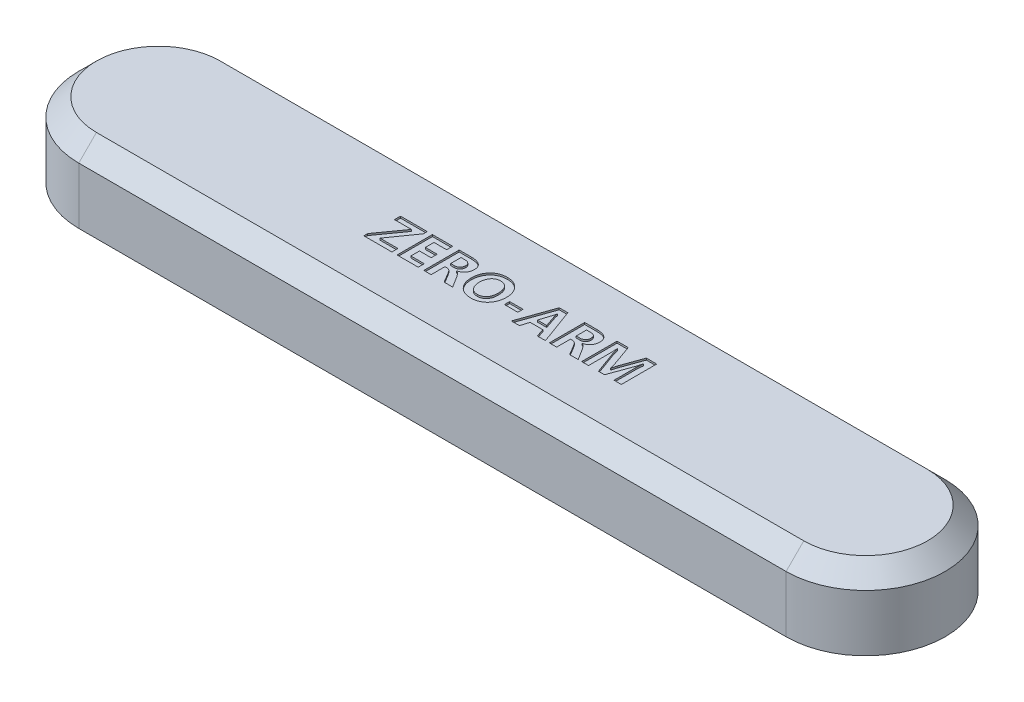
SolidWorks part; units mm, degrees
ref_plane "前视基准面" through (0, 0, 0) normal (0, 0, 1) x (1, 0, 0)
ref_plane "上视基准面" through (0, 0, 0) normal (0, 1, 0) x (1, 0, 0)
ref_plane "右视基准面" through (0, 0, 0) normal (1, 0, 0) x (0, 0, -1)
other "Configuration Table"
sketch "草图1" plane through (0, 0, 0) normal (0, 1, 0) x (1, 0, 0)
  line L1 (-100, 22.5) -> (100, 22.5)
  line L2 (-100, 22.5) -> (-100, -22.5)
  line L3 (-100, -22.5) -> (100, -22.5)
  line L4 (100, 22.5) -> (100, -22.5)
  line L5 (-100, 22.5) -> (100, -22.5) construction
  line L6 (-100, -22.5) -> (100, 22.5) construction
  circle A0 centre (-100, 0) radius 22.5
  circle A1 centre (100, 0) radius 22.5
  point P0 (0, 0)
  dimension "D1" = 200
  dimension "D2" = 45
extrude "凸台-拉伸1" add sketch "草图1" along normal blind 21 contours L2 A0 | L2 A0 | A1 L1 A0 L3 | L4 A1 | L4 A1
chamfer "倒角1" distance 5 angle 45 4 edges at (0, 21, -22.5) (-122.5, 21, 0) (122.5, 21, 0) (0, 21, 22.5)
shell "抽壳1" thickness 2.5
sketch "草图2" plane through (0, 0, 0) normal (0, -1, 0) x (1, 0, 0)
  line L0 (-100, -20) -> (100, -20) construction
  line L1 (-100, 20) -> (100, 20) construction
  line L2 (-100, -20) -> (100, -20)
  line L3 (-100, 20) -> (100, 20)
  line L4 (-100, -21.2) -> (100, -21.2)
  line L5 (-100, 21.2) -> (100, 21.2)
  arc A0 (100, -20) -> (100, 20) centre (100, 0) ccw construction
  arc A1 (-100, 20) -> (-100, -20) centre (-100, 0) ccw construction
  arc A2 (100, -20) -> (100, 20) centre (100, 0) ccw
  arc A3 (-100, 20) -> (-100, -20) centre (-100, 0) ccw
  arc A4 (-100, 21.2) -> (-100, -21.2) centre (-100, 0) ccw
  arc A5 (100, -21.2) -> (100, 21.2) centre (100, 0) ccw
  dimension "D1" = 1.2
extrude "切除-拉伸2" cut sketch "草图2" against normal blind 1.2
sketch "草图4" plane through (0, 18.5, 0) normal (0, -1, 0) x (1, 0, 0)
  line L0 (0, 0) -> (-15, 0) construction
  line L2 (-18.1177, 0) -> (-16.5588, -2.7) construction
  line L3 (-16.5588, -2.7) -> (-13.4412, -2.7) construction
  line L4 (-13.4412, -2.7) -> (-11.8823, 0) construction
  line L5 (-11.8823, 0) -> (-13.4412, 2.7) construction
  line L6 (-13.4412, 2.7) -> (-16.5588, 2.7) construction
  line L7 (-16.5588, 2.7) -> (-18.1177, 0) construction
  circle A0 centre (-15, 0) radius 5
  circle A1 centre (-15, 0) radius 2.7 construction
  dimension "D2" = 5.4
  dimension "D3" = 10
  dimension "D1" = 15
extrude "凸台-拉伸3" add sketch "草图4" along normal offset from surface (17.5 mm away) 1 up to face at (0, 0, 0)
sketch "草图5" plane through (0, 1, 0) normal (0, -1, 0) x (1, 0, 0)
  circle A0 centre (-15, 0) radius 1.6
  dimension "D1" = 3.2
extrude "切除-拉伸3" cut sketch "草图5" against normal blind 10
sketch "草图6" plane through (0, 1, 0) normal (0, -1, 0) x (1, 0, 0)
  line L1 (-13.4123, -2.75) -> (-11.8246, 0)
  line L2 (-11.8246, 0) -> (-13.4123, 2.75)
  line L3 (-13.4123, 2.75) -> (-16.5877, 2.75)
  line L4 (-16.5877, 2.75) -> (-18.1754, 0)
  line L5 (-18.1754, 0) -> (-16.5877, -2.75)
  line L6 (-16.5877, -2.75) -> (-13.4123, -2.75)
  circle A0 centre (-15, 0) radius 2.75 construction
  dimension "D1" = 5.5
extrude "切除-拉伸4" cut sketch "草图6" against normal blind 2.4
mirror "镜向1" about plane through (0, 0, 0) normal (1, 0, 0) of "切除-拉伸4", "凸台-拉伸3", "切除-拉伸3"
sketch "草图7" plane through (0, 21, 0) normal (0, 1, 0) x (1, 0, 0)
  line L0 (0, 0) -> (0, -5) construction
  line L1 (80, -5) -> (-80, -5) construction
  text T0 "<b>ZERO-ARM</b>" font "微软雅黑" height 10
  point P6 (0, 0)
  point P7 (0, -5)
  dimension "D1" = 160
  dimension "D2" = 5
extrude "切除-拉伸5" cut sketch "草图7" against normal blind 0.5
